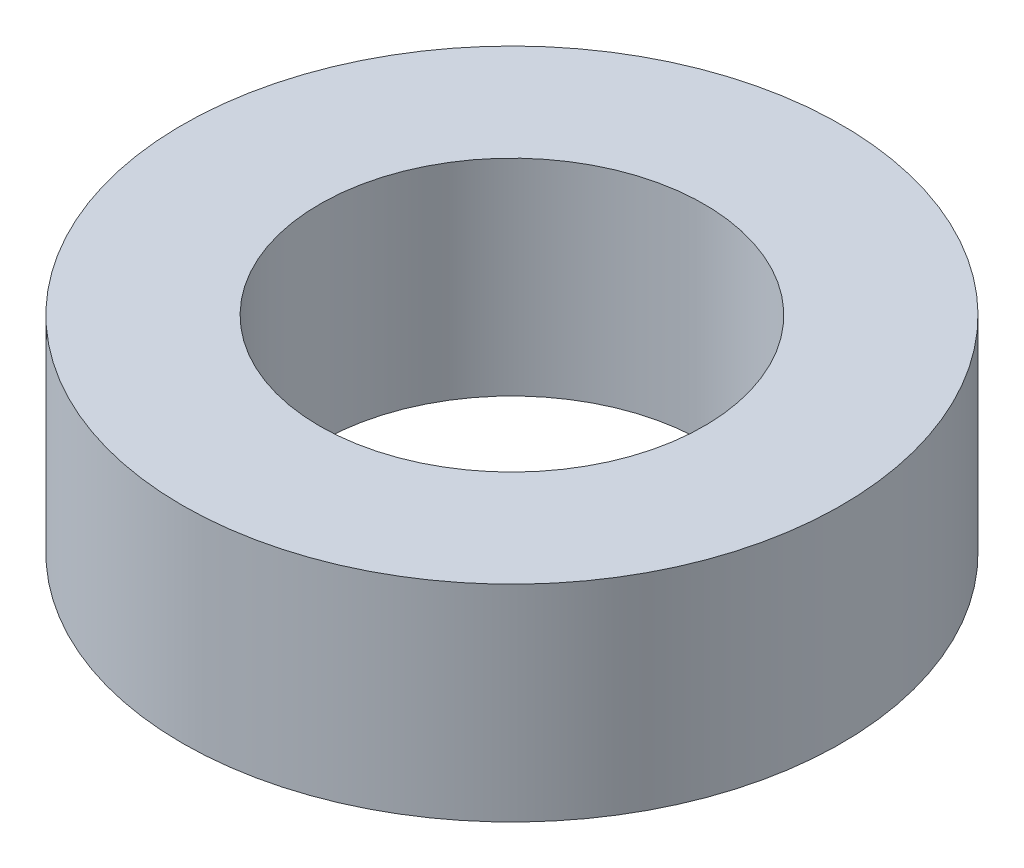
SolidWorks part; units mm, degrees
ref_plane "Ebene vorne" through (0, 0, 0) normal (0, 0, 1) x (1, 0, 0)
ref_plane "Ebene oben" through (0, 0, 0) normal (0, 1, 0) x (1, 0, 0)
ref_plane "Ebene rechts" through (0, 0, 0) normal (1, 0, 0) x (0, 0, -1)
sketch "Skizze1" plane through (0, 0, 0) normal (0, 1, 0) x (1, 0, 0)
  circle A0 centre (0, 0) radius 1.4
  circle A1 centre (0, 0) radius 2.4
extrude "Aufsatz-Linear austragen1" add sketch "Skizze1" along normal blind 1.5
